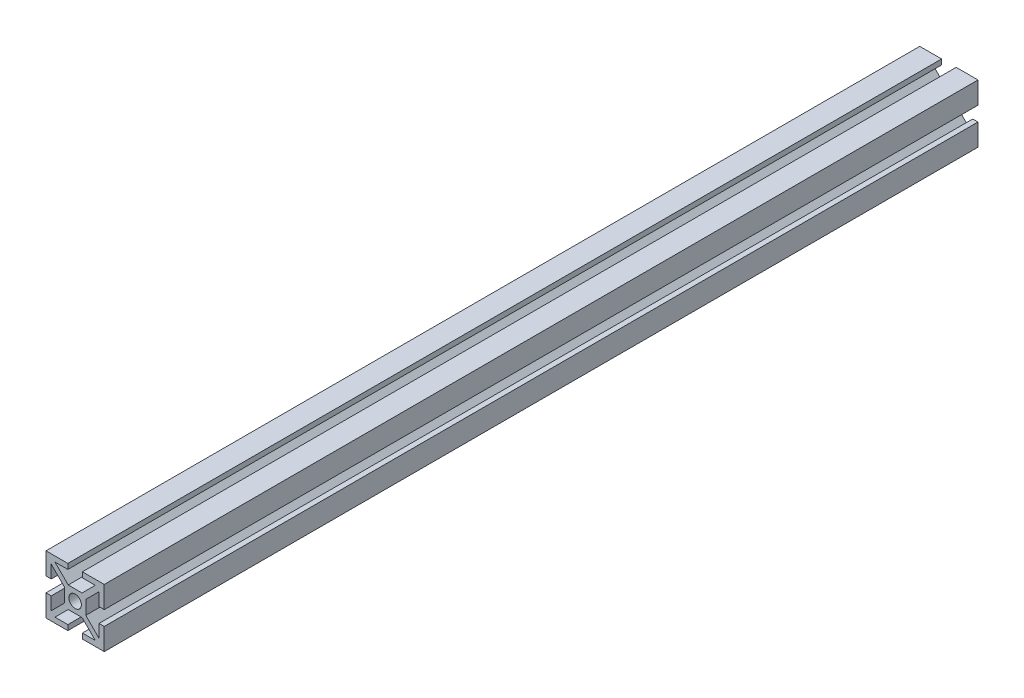
SolidWorks part; units mm, degrees
ref_plane "Plan de face" through (0, 0, 0) normal (0, 0, 1) x (1, 0, 0)
ref_plane "Plan de dessus" through (0, 0, 0) normal (0, 1, 0) x (1, 0, 0)
ref_plane "Plan de droite" through (0, 0, 0) normal (1, 0, 0) x (0, 0, -1)
sketch "Esquisse1" plane through (0, 0, 0) normal (0, 0, 1) x (1, 0, 0)
  line L0 (20, 12.5) -> (18.2, 12.5)
  line L1 (0, 0) -> (7.5, 0)
  line L2 (0, 0) -> (0, 7.5)
  line L3 (0, 20) -> (7.5, 20)
  line L4 (20, 0) -> (20, 7.5)
  line L5 (18.2, 12.5) -> (18.2, 16.9272)
  line L6 (0, 0) -> (20, 20) construction
  line L7 (13.65, 12.3772) -> (13.65, 10)
  line L8 (13.65, 12.3772) -> (18.2, 16.9272)
  line L9 (12.5, 20) -> (12.5, 18.2)
  line L10 (12.5, 18.2) -> (16.9272, 18.2)
  line L11 (12.3772, 13.65) -> (16.9272, 18.2)
  line L12 (12.3772, 13.65) -> (10, 13.65)
  line L13 (13.65, 7.6228) -> (13.65, 10)
  line L14 (13.65, 7.6228) -> (18.2, 3.0728)
  line L15 (18.2, 7.5) -> (18.2, 3.0728)
  line L16 (20, 7.5) -> (18.2, 7.5)
  line L17 (12.5, 1.8) -> (16.9272, 1.8)
  line L18 (12.3772, 6.35) -> (16.9272, 1.8)
  line L19 (12.5, 0) -> (12.5, 1.8)
  line L20 (12.3772, 6.35) -> (10, 6.35)
  line L21 (7.6228, 6.35) -> (10, 6.35)
  line L22 (7.6228, 6.35) -> (3.0728, 1.8)
  line L23 (7.5, 1.8) -> (3.0728, 1.8)
  line L24 (7.5, 0) -> (7.5, 1.8)
  line L25 (1.8, 7.5) -> (1.8, 3.0728)
  line L26 (6.35, 7.6228) -> (1.8, 3.0728)
  line L27 (0, 7.5) -> (1.8, 7.5)
  line L28 (6.35, 7.6228) -> (6.35, 10)
  line L29 (6.35, 12.3772) -> (6.35, 10)
  line L30 (6.35, 12.3772) -> (1.8, 16.9272)
  line L31 (1.8, 12.5) -> (1.8, 16.9272)
  line L32 (0, 12.5) -> (1.8, 12.5)
  line L33 (7.5, 18.2) -> (3.0728, 18.2)
  line L34 (7.6228, 13.65) -> (3.0728, 18.2)
  line L35 (7.5, 20) -> (7.5, 18.2)
  line L36 (7.6228, 13.65) -> (10, 13.65)
  line L37 (20, 12.5) -> (20, 20)
  line L38 (12.5, 20) -> (20, 20)
  line L39 (0, 12.5) -> (0, 20)
  line L40 (12.5, 0) -> (20, 0)
  circle A0 centre (10, 10) radius 2.15
  point P11 (0, 0)
  point P18 (0, 0)
  point P19 (0, 0)
  point P20 (10.7237, 10.7237)
  point P51 (10, 10)
  dimension "D2" = 4.3
  dimension "D1" = 20
  dimension "D3" = 1.8
  dimension "D4" = 5
  dimension "D5" = 6.35
  dimension "D6" = 1.8
  dimension "D7" = 4
extrude "Boss.-Extru.1" add sketch "Esquisse1" along normal blind 300
